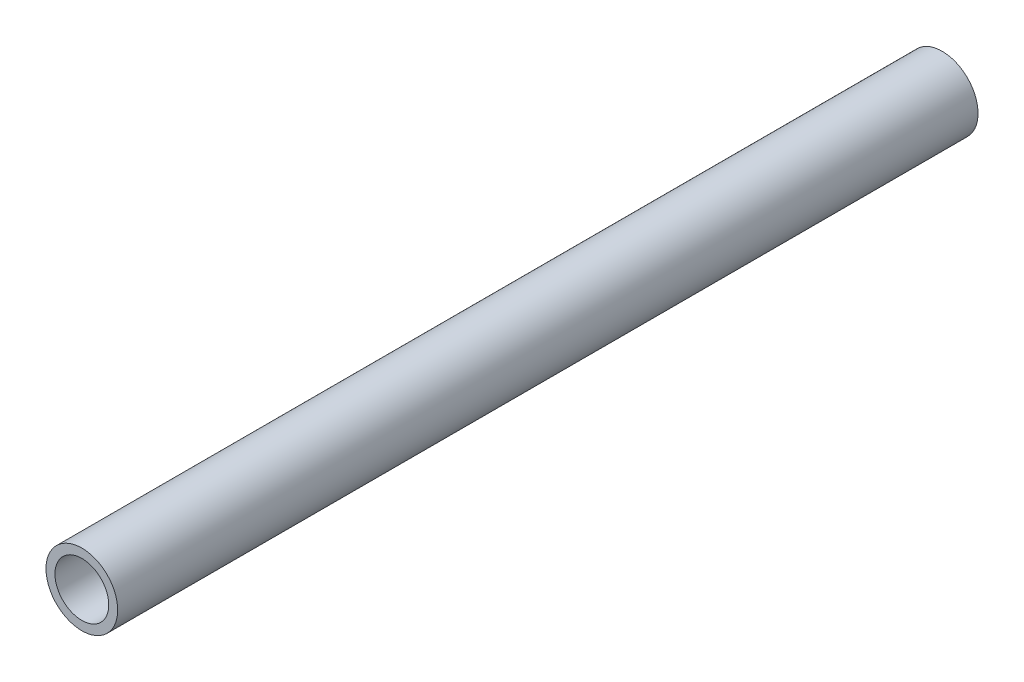
SolidWorks part; units mm, degrees
ref_plane "Front Plane" through (0, 0, 0) normal (0, 0, 1) x (1, 0, 0)
ref_plane "Top Plane" through (0, 0, 0) normal (0, 1, 0) x (1, 0, 0)
ref_plane "Right Plane" through (0, 0, 0) normal (1, 0, 0) x (0, 0, -1)
sketch "Sketch1" plane through (0, 0, 0) normal (0, 0, 1) x (1, 0, 0)
  circle A0 centre (0, 0) radius 6.35
  circle A1 centre (0, 0) radius 4.7625
  dimension "D1" = 12.7
  dimension "D2" = 9.525
extrude "Boss-Extrude1" add sketch "Sketch1" along normal blind 152.4
ref_plane "Plane1" through (6.35, 0, 0) normal (1, 0, 0) x (0, 0, -1)
